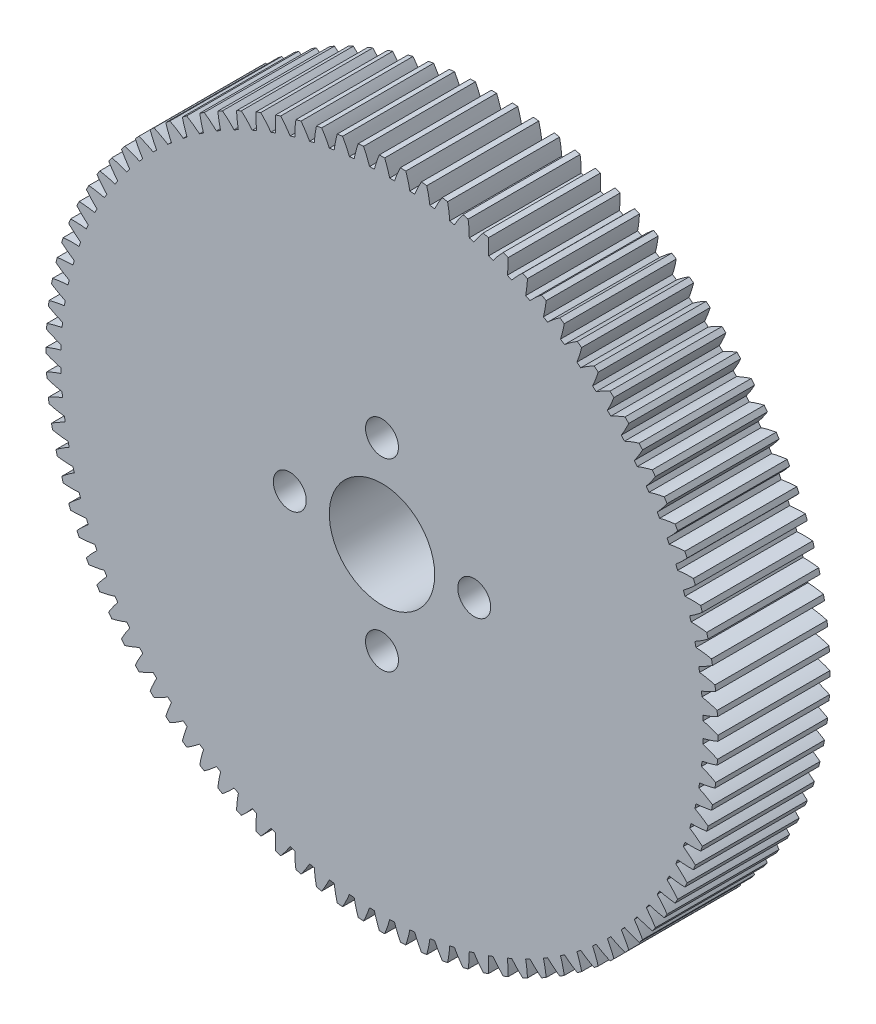
SolidWorks part; units mm, degrees
material "ABS"
ref_plane "Front Plane" through (0, 0, 0) normal (0, 0, 1) x (1, 0, 0)
ref_plane "Top Plane" through (0, 0, 0) normal (0, 1, 0) x (1, 0, 0)
ref_plane "Right Plane" through (0, 0, 0) normal (1, 0, 0) x (0, 0, -1)
ref_plane "Plane1" through (0, 0, 4) normal (0, 0, 1) x (1, 0, 0)
sketch "Sketch1" plane through (0, 0, 4) normal (0, 0, 1) x (1, 0, 0)
  line L0 (25.4992, -0.2018) -> (25.4992, 0.2018)
  line L1 (25.4616, 1.3997) -> (25.4362, 1.8025)
  line L2 (25.3234, 2.9957) -> (25.2728, 3.3961)
  line L3 (25.0854, 4.5799) -> (25.0097, 4.9763)
  line L4 (24.7483, 6.1459) -> (24.6479, 6.5369)
  line L5 (24.3135, 7.6878) -> (24.1888, 8.0716)
  line L6 (23.7828, 9.1993) -> (23.6343, 9.5745)
  line L7 (23.1583, 10.6744) -> (22.9864, 11.0396)
  line L8 (22.4423, 12.1075) -> (22.2479, 12.4612)
  line L9 (21.6378, 13.4928) -> (21.4216, 13.8335)
  line L10 (20.7479, 14.8248) -> (20.5107, 15.1513)
  line L11 (19.7761, 16.0983) -> (19.5188, 16.4093)
  line L12 (18.7263, 17.3083) -> (18.45, 17.6025)
  line L13 (17.6025, 18.45) -> (17.3083, 18.7263)
  line L14 (16.4093, 19.5188) -> (16.0983, 19.7761)
  line L15 (15.1513, 20.5107) -> (14.8248, 20.7479)
  line L16 (13.8335, 21.4216) -> (13.4928, 21.6378)
  line L17 (12.4612, 22.2479) -> (12.1075, 22.4423)
  line L18 (11.0396, 22.9864) -> (10.6744, 23.1583)
  line L19 (9.5745, 23.6343) -> (9.1993, 23.7828)
  line L20 (8.0716, 24.1888) -> (7.6878, 24.3135)
  line L21 (6.5369, 24.6479) -> (6.1459, 24.7483)
  line L22 (4.9763, 25.0097) -> (4.5799, 25.0854)
  line L23 (3.3961, 25.2728) -> (2.9957, 25.3234)
  line L24 (1.8025, 25.4362) -> (1.3997, 25.4616)
  line L25 (0.2018, 25.4992) -> (-0.2018, 25.4992)
  line L26 (-1.3997, 25.4616) -> (-1.8025, 25.4362)
  line L27 (-2.9957, 25.3234) -> (-3.3961, 25.2728)
  line L28 (-4.5799, 25.0854) -> (-4.9763, 25.0097)
  line L29 (-6.1459, 24.7483) -> (-6.5369, 24.6479)
  line L30 (-7.6878, 24.3135) -> (-8.0716, 24.1888)
  line L31 (-9.1993, 23.7828) -> (-9.5745, 23.6343)
  line L32 (-10.6744, 23.1583) -> (-11.0396, 22.9864)
  line L33 (-12.1075, 22.4423) -> (-12.4612, 22.2479)
  line L34 (-13.4928, 21.6378) -> (-13.8335, 21.4216)
  line L35 (-14.8248, 20.7479) -> (-15.1513, 20.5107)
  line L36 (-16.0983, 19.7761) -> (-16.4093, 19.5188)
  line L37 (-17.3083, 18.7263) -> (-17.6025, 18.45)
  line L38 (-18.45, 17.6025) -> (-18.7263, 17.3083)
  line L39 (-19.5188, 16.4093) -> (-19.7761, 16.0983)
  line L40 (-20.5107, 15.1513) -> (-20.7479, 14.8248)
  line L41 (-21.4216, 13.8335) -> (-21.6378, 13.4928)
  line L42 (-22.2479, 12.4612) -> (-22.4423, 12.1075)
  line L43 (-22.9864, 11.0396) -> (-23.1583, 10.6744)
  line L44 (-23.6343, 9.5745) -> (-23.7828, 9.1993)
  line L45 (-24.1888, 8.0716) -> (-24.3135, 7.6878)
  line L46 (-24.6479, 6.5369) -> (-24.7483, 6.1459)
  line L47 (-25.0097, 4.9763) -> (-25.0854, 4.5799)
  line L48 (-25.2728, 3.3961) -> (-25.3234, 2.9957)
  line L49 (-25.4362, 1.8025) -> (-25.4616, 1.3997)
  line L50 (-25.4992, 0.2018) -> (-25.4992, -0.2018)
  line L51 (-25.4616, -1.3997) -> (-25.4362, -1.8025)
  line L52 (-25.3234, -2.9957) -> (-25.2728, -3.3961)
  line L53 (-25.0854, -4.5799) -> (-25.0097, -4.9763)
  line L54 (-24.7483, -6.1459) -> (-24.6479, -6.5369)
  line L55 (-24.3135, -7.6878) -> (-24.1888, -8.0716)
  line L56 (-23.7828, -9.1993) -> (-23.6343, -9.5745)
  line L57 (-23.1583, -10.6744) -> (-22.9864, -11.0396)
  line L58 (-22.4423, -12.1075) -> (-22.2479, -12.4612)
  line L59 (-21.6378, -13.4928) -> (-21.4216, -13.8335)
  line L60 (-20.7479, -14.8248) -> (-20.5107, -15.1513)
  line L61 (-19.7761, -16.0983) -> (-19.5188, -16.4093)
  line L62 (-18.7263, -17.3083) -> (-18.45, -17.6025)
  line L63 (-17.6025, -18.45) -> (-17.3083, -18.7263)
  line L64 (-16.4093, -19.5188) -> (-16.0983, -19.7761)
  line L65 (-15.1513, -20.5107) -> (-14.8248, -20.7479)
  line L66 (-13.8335, -21.4216) -> (-13.4928, -21.6378)
  line L67 (-12.4612, -22.2479) -> (-12.1075, -22.4423)
  line L68 (-11.0396, -22.9864) -> (-10.6744, -23.1583)
  line L69 (-9.5745, -23.6343) -> (-9.1993, -23.7828)
  line L70 (-8.0716, -24.1888) -> (-7.6878, -24.3135)
  line L71 (-6.5369, -24.6479) -> (-6.1459, -24.7483)
  line L72 (-4.9763, -25.0097) -> (-4.5799, -25.0854)
  line L73 (-3.3961, -25.2728) -> (-2.9957, -25.3234)
  line L74 (-1.8025, -25.4362) -> (-1.3997, -25.4616)
  line L75 (-0.2018, -25.4992) -> (0.2018, -25.4992)
  line L76 (1.3997, -25.4616) -> (1.8025, -25.4362)
  line L77 (2.9957, -25.3234) -> (3.3961, -25.2728)
  line L78 (4.5799, -25.0854) -> (4.9763, -25.0097)
  line L79 (6.1459, -24.7483) -> (6.5369, -24.6479)
  line L80 (7.6878, -24.3135) -> (8.0716, -24.1888)
  line L81 (9.1993, -23.7828) -> (9.5745, -23.6343)
  line L82 (10.6744, -23.1583) -> (11.0396, -22.9864)
  line L83 (12.1075, -22.4423) -> (12.4612, -22.2479)
  line L84 (13.4928, -21.6378) -> (13.8335, -21.4216)
  line L85 (14.8248, -20.7479) -> (15.1513, -20.5107)
  line L86 (16.0983, -19.7761) -> (16.4093, -19.5188)
  line L87 (17.3083, -18.7263) -> (17.6025, -18.45)
  line L88 (18.45, -17.6025) -> (18.7263, -17.3083)
  line L89 (19.5188, -16.4093) -> (19.7761, -16.0983)
  line L90 (20.5107, -15.1513) -> (20.7479, -14.8248)
  line L91 (21.4216, -13.8335) -> (21.6378, -13.4928)
  line L92 (22.2479, -12.4612) -> (22.4423, -12.1075)
  line L93 (22.9864, -11.0396) -> (23.1583, -10.6744)
  line L94 (23.6343, -9.5745) -> (23.7828, -9.1993)
  line L95 (24.1888, -8.0716) -> (24.3135, -7.6878)
  line L96 (24.6479, -6.5369) -> (24.7483, -6.1459)
  line L97 (25.0097, -4.9763) -> (25.0854, -4.5799)
  line L98 (25.2728, -3.3961) -> (25.3234, -2.9957)
  line L99 (25.4362, -1.8025) -> (25.4616, -1.3997)
  arc A0 (24.3565, -0.9497) -> (24.3681, -0.5815) centre (0, 0) ccw
  arc A1 (24.3681, -0.5815) -> (25.4992, -0.2018) centre (22.3084, 7.4288) ccw
  arc A2 (25.4992, 0.2018) -> (24.3681, 0.5815) centre (22.3272, -7.3729) ccw
  arc A3 (24.3681, 0.5815) -> (24.3565, 0.9497) centre (0, 0) ccw
  arc A4 (24.3565, 0.9497) -> (25.4616, 1.3997) centre (21.7979, 8.8149) ccw
  arc A5 (25.4362, 1.8025) -> (24.2835, 2.1104) centre (22.7461, -5.9564) ccw
  arc A6 (24.2835, 2.1104) -> (24.2488, 2.4772) centre (0, 0) ccw
  arc A7 (24.2488, 2.4772) -> (25.3234, 2.9957) centre (21.2014, 10.1662) ccw
  arc A8 (25.2728, 3.3961) -> (24.103, 3.631) centre (23.0752, -4.5164) ccw
  arc A9 (24.103, 3.631) -> (24.0454, 3.9949) centre (0, 0) ccw
  arc A10 (24.0454, 3.9949) -> (25.0854, 4.5799) centre (20.5213, 11.4774) ccw
  arc A11 (25.0097, 4.9763) -> (23.8275, 5.1373) centre (23.3132, -3.0586) ccw
  arc A12 (23.8275, 5.1373) -> (23.7471, 5.4969) centre (0, 0) ccw
  arc A13 (23.7471, 5.4969) -> (24.7483, 6.1459) centre (19.7601, 12.7433) ccw
  arc A14 (24.6479, 6.5369) -> (23.4579, 6.6233) centre (23.4593, -1.5887) ccw
  arc A15 (23.4579, 6.6233) -> (23.3551, 6.9771) centre (0, 0) ccw
  arc A16 (23.3551, 6.9771) -> (24.3135, 7.6878) centre (18.921, 13.9589) ccw
  arc A17 (24.1888, 8.0716) -> (22.9957, 8.0832) centre (23.5128, -0.1125) ccw
  arc A18 (22.9957, 8.0832) -> (22.8709, 8.4298) centre (0, 0) ccw
  arc A19 (22.8709, 8.4298) -> (23.7828, 9.1993) centre (18.0071, 15.1194) ccw
  arc A20 (23.6343, 9.5745) -> (22.4428, 9.5112) centre (23.4734, 1.3641) ccw
  arc A21 (22.4428, 9.5112) -> (22.2965, 9.8493) centre (0, 0) ccw
  arc A22 (22.2965, 9.8493) -> (23.1583, 10.6744) centre (17.0222, 16.2202) ccw
  arc A23 (22.9864, 11.0396) -> (21.8013, 10.9016) centre (23.3415, 2.8353) ccw
  arc A24 (21.8013, 10.9016) -> (21.634, 11.2298) centre (0, 0) ccw
  arc A25 (21.634, 11.2298) -> (22.4423, 12.1075) centre (15.9702, 17.257) ccw
  arc A26 (22.2479, 12.4612) -> (21.0738, 12.249) centre (23.1174, 4.2953) ccw
  arc A27 (21.0738, 12.249) -> (20.8862, 12.5661) centre (0, 0) ccw
  arc A28 (20.8862, 12.5661) -> (21.6378, 13.4928) centre (14.8551, 18.2258) ccw
  arc A29 (21.4216, 13.8335) -> (20.263, 13.548) centre (22.8021, 5.7384) ccw
  arc A30 (20.263, 13.548) -> (20.056, 13.8527) centre (0, 0) ccw
  arc A31 (20.056, 13.8527) -> (20.7479, 14.8248) centre (13.6814, 19.1226) ccw
  arc A32 (20.5107, 15.1513) -> (19.3724, 14.7936) centre (22.3967, 7.1588) ccw
  arc A33 (19.3724, 14.7936) -> (19.1466, 15.0847) centre (0, 0) ccw
  arc A34 (19.1466, 15.0847) -> (19.7761, 16.0983) centre (12.4537, 19.9439) ccw
  arc A35 (19.5188, 16.4093) -> (18.4052, 15.9808) centre (21.903, 8.551) ccw
  arc A36 (18.4052, 15.9808) -> (18.1616, 16.2572) centre (0, 0) ccw
  arc A37 (18.1616, 16.2572) -> (18.7263, 17.3083) centre (11.1768, 20.6865) ccw
  arc A38 (18.45, 17.6025) -> (17.3655, 17.105) centre (21.3229, 9.9094) ccw
  arc A39 (17.3655, 17.105) -> (17.105, 17.3655) centre (0, 0) ccw
  arc A40 (17.105, 17.3655) -> (17.6025, 18.45) centre (9.8558, 21.3475) ccw
  arc A41 (17.3083, 18.7263) -> (16.2572, 18.1616) centre (20.6586, 11.2287) ccw
  arc A42 (16.2572, 18.1616) -> (15.9808, 18.4052) centre (0, 0) ccw
  arc A43 (15.9808, 18.4052) -> (16.4093, 19.5188) centre (8.496, 21.9242) ccw
  arc A44 (16.0983, 19.7761) -> (15.0847, 19.1466) centre (19.9128, 12.5037) ccw
  arc A45 (15.0847, 19.1466) -> (14.7936, 19.3724) centre (0, 0) ccw
  arc A46 (14.7936, 19.3724) -> (15.1513, 20.5107) centre (7.1026, 22.4144) ccw
  arc A47 (14.8248, 20.7479) -> (13.8527, 20.056) centre (19.0884, 13.7294) ccw
  arc A48 (13.8527, 20.056) -> (13.548, 20.263) centre (0, 0) ccw
  arc A49 (13.548, 20.263) -> (13.8335, 21.4216) centre (5.6811, 22.8162) ccw
  arc A50 (13.4928, 21.6378) -> (12.5661, 20.8862) centre (18.1886, 14.9009) ccw
  arc A51 (12.5661, 20.8862) -> (12.249, 21.0738) centre (0, 0) ccw
  arc A52 (12.249, 21.0738) -> (12.4612, 22.2479) centre (4.2373, 23.1279) ccw
  arc A53 (12.1075, 22.4423) -> (11.2298, 21.634) centre (17.2171, 16.0136) ccw
  arc A54 (11.2298, 21.634) -> (10.9016, 21.8013) centre (0, 0) ccw
  arc A55 (10.9016, 21.8013) -> (11.0396, 22.9864) centre (2.7767, 23.3483) ccw
  arc A56 (10.6744, 23.1583) -> (9.8493, 22.2965) centre (16.1776, 17.063) ccw
  arc A57 (9.8493, 22.2965) -> (9.5112, 22.4428) centre (0, 0) ccw
  arc A58 (9.5112, 22.4428) -> (9.5745, 23.6343) centre (1.3052, 23.4766) ccw
  arc A59 (9.1993, 23.7828) -> (8.4298, 22.8709) centre (15.0743, 18.0452) ccw
  arc A60 (8.4298, 22.8709) -> (8.0832, 22.9957) centre (0, 0) ccw
  arc A61 (8.0832, 22.9957) -> (8.0716, 24.1888) centre (-0.1715, 23.5122) ccw
  arc A62 (7.6878, 24.3135) -> (6.9771, 23.3551) centre (13.9115, 18.9561) ccw
  arc A63 (6.9771, 23.3551) -> (6.6233, 23.4579) centre (0, 0) ccw
  arc A64 (6.6233, 23.4579) -> (6.5369, 24.6479) centre (-1.6475, 23.455) ccw
  arc A65 (6.1459, 24.7483) -> (5.4969, 23.7471) centre (12.6938, 19.7922) ccw
  arc A66 (5.4969, 23.7471) -> (5.1373, 23.8275) centre (0, 0) ccw
  arc A67 (5.1373, 23.8275) -> (4.9763, 25.0097) centre (-3.117, 23.3053) ccw
  arc A68 (4.5799, 25.0854) -> (3.9949, 24.0454) centre (11.426, 20.5502) ccw
  arc A69 (3.9949, 24.0454) -> (3.631, 24.103) centre (0, 0) ccw
  arc A70 (3.631, 24.103) -> (3.3961, 25.2728) centre (-4.5742, 23.0636) ccw
  arc A71 (2.9957, 25.3234) -> (2.4772, 24.2488) centre (10.1131, 21.2271) ccw
  arc A72 (2.4772, 24.2488) -> (2.1104, 24.2835) centre (0, 0) ccw
  arc A73 (2.1104, 24.2835) -> (1.8025, 25.4362) centre (-6.0134, 22.7309) ccw
  arc A74 (1.3997, 25.4616) -> (0.9497, 24.3565) centre (8.7603, 21.8202) ccw
  arc A75 (0.9497, 24.3565) -> (0.5815, 24.3681) centre (0, 0) ccw
  arc A76 (0.5815, 24.3681) -> (0.2018, 25.4992) centre (-7.4288, 22.3084) ccw
  arc A77 (-0.2018, 25.4992) -> (-0.5815, 24.3681) centre (7.3729, 22.3272) ccw
  arc A78 (-0.5815, 24.3681) -> (-0.9497, 24.3565) centre (0, 0) ccw
  arc A79 (-0.9497, 24.3565) -> (-1.3997, 25.4616) centre (-8.8149, 21.7979) ccw
  arc A80 (-1.8025, 25.4362) -> (-2.1104, 24.2835) centre (5.9564, 22.7461) ccw
  arc A81 (-2.1104, 24.2835) -> (-2.4772, 24.2488) centre (0, 0) ccw
  arc A82 (-2.4772, 24.2488) -> (-2.9957, 25.3234) centre (-10.1662, 21.2014) ccw
  arc A83 (-3.3961, 25.2728) -> (-3.631, 24.103) centre (4.5164, 23.0752) ccw
  arc A84 (-3.631, 24.103) -> (-3.9949, 24.0454) centre (0, 0) ccw
  arc A85 (-3.9949, 24.0454) -> (-4.5799, 25.0854) centre (-11.4774, 20.5213) ccw
  arc A86 (-4.9763, 25.0097) -> (-5.1373, 23.8275) centre (3.0586, 23.3132) ccw
  arc A87 (-5.1373, 23.8275) -> (-5.4969, 23.7471) centre (0, 0) ccw
  arc A88 (-5.4969, 23.7471) -> (-6.1459, 24.7483) centre (-12.7433, 19.7601) ccw
  arc A89 (-6.5369, 24.6479) -> (-6.6233, 23.4579) centre (1.5887, 23.4593) ccw
  arc A90 (-6.6233, 23.4579) -> (-6.9771, 23.3551) centre (0, 0) ccw
  arc A91 (-6.9771, 23.3551) -> (-7.6878, 24.3135) centre (-13.9589, 18.921) ccw
  arc A92 (-8.0716, 24.1888) -> (-8.0832, 22.9957) centre (0.1125, 23.5128) ccw
  arc A93 (-8.0832, 22.9957) -> (-8.4298, 22.8709) centre (0, 0) ccw
  arc A94 (-8.4298, 22.8709) -> (-9.1993, 23.7828) centre (-15.1194, 18.0071) ccw
  arc A95 (-9.5745, 23.6343) -> (-9.5112, 22.4428) centre (-1.3641, 23.4734) ccw
  arc A96 (-9.5112, 22.4428) -> (-9.8493, 22.2965) centre (0, 0) ccw
  arc A97 (-9.8493, 22.2965) -> (-10.6744, 23.1583) centre (-16.2202, 17.0222) ccw
  arc A98 (-11.0396, 22.9864) -> (-10.9016, 21.8013) centre (-2.8353, 23.3415) ccw
  arc A99 (-10.9016, 21.8013) -> (-11.2298, 21.634) centre (0, 0) ccw
  arc A100 (-11.2298, 21.634) -> (-12.1075, 22.4423) centre (-17.257, 15.9702) ccw
  arc A101 (-12.4612, 22.2479) -> (-12.249, 21.0738) centre (-4.2953, 23.1174) ccw
  arc A102 (-12.249, 21.0738) -> (-12.5661, 20.8862) centre (0, 0) ccw
  arc A103 (-12.5661, 20.8862) -> (-13.4928, 21.6378) centre (-18.2258, 14.8551) ccw
  arc A104 (-13.8335, 21.4216) -> (-13.548, 20.263) centre (-5.7384, 22.8021) ccw
  arc A105 (-13.548, 20.263) -> (-13.8527, 20.056) centre (0, 0) ccw
  arc A106 (-13.8527, 20.056) -> (-14.8248, 20.7479) centre (-19.1226, 13.6814) ccw
  arc A107 (-15.1513, 20.5107) -> (-14.7936, 19.3724) centre (-7.1588, 22.3967) ccw
  arc A108 (-14.7936, 19.3724) -> (-15.0847, 19.1466) centre (0, 0) ccw
  arc A109 (-15.0847, 19.1466) -> (-16.0983, 19.7761) centre (-19.9439, 12.4537) ccw
  arc A110 (-16.4093, 19.5188) -> (-15.9808, 18.4052) centre (-8.551, 21.903) ccw
  arc A111 (-15.9808, 18.4052) -> (-16.2572, 18.1616) centre (0, 0) ccw
  arc A112 (-16.2572, 18.1616) -> (-17.3083, 18.7263) centre (-20.6865, 11.1768) ccw
  arc A113 (-17.6025, 18.45) -> (-17.105, 17.3655) centre (-9.9094, 21.3229) ccw
  arc A114 (-17.105, 17.3655) -> (-17.3655, 17.105) centre (0, 0) ccw
  arc A115 (-17.3655, 17.105) -> (-18.45, 17.6025) centre (-21.3475, 9.8558) ccw
  arc A116 (-18.7263, 17.3083) -> (-18.1616, 16.2572) centre (-11.2287, 20.6586) ccw
  arc A117 (-18.1616, 16.2572) -> (-18.4052, 15.9808) centre (0, 0) ccw
  arc A118 (-18.4052, 15.9808) -> (-19.5188, 16.4093) centre (-21.9242, 8.496) ccw
  arc A119 (-19.7761, 16.0983) -> (-19.1466, 15.0847) centre (-12.5037, 19.9128) ccw
  arc A120 (-19.1466, 15.0847) -> (-19.3724, 14.7936) centre (0, 0) ccw
  arc A121 (-19.3724, 14.7936) -> (-20.5107, 15.1513) centre (-22.4144, 7.1026) ccw
  arc A122 (-20.7479, 14.8248) -> (-20.056, 13.8527) centre (-13.7294, 19.0884) ccw
  arc A123 (-20.056, 13.8527) -> (-20.263, 13.548) centre (0, 0) ccw
  arc A124 (-20.263, 13.548) -> (-21.4216, 13.8335) centre (-22.8162, 5.6811) ccw
  arc A125 (-21.6378, 13.4928) -> (-20.8862, 12.5661) centre (-14.9009, 18.1886) ccw
  arc A126 (-20.8862, 12.5661) -> (-21.0738, 12.249) centre (0, 0) ccw
  arc A127 (-21.0738, 12.249) -> (-22.2479, 12.4612) centre (-23.1279, 4.2373) ccw
  arc A128 (-22.4423, 12.1075) -> (-21.634, 11.2298) centre (-16.0136, 17.2171) ccw
  arc A129 (-21.634, 11.2298) -> (-21.8013, 10.9016) centre (0, 0) ccw
  arc A130 (-21.8013, 10.9016) -> (-22.9864, 11.0396) centre (-23.3483, 2.7767) ccw
  arc A131 (-23.1583, 10.6744) -> (-22.2965, 9.8493) centre (-17.063, 16.1776) ccw
  arc A132 (-22.2965, 9.8493) -> (-22.4428, 9.5112) centre (0, 0) ccw
  arc A133 (-22.4428, 9.5112) -> (-23.6343, 9.5745) centre (-23.4766, 1.3052) ccw
  arc A134 (-23.7828, 9.1993) -> (-22.8709, 8.4298) centre (-18.0452, 15.0743) ccw
  arc A135 (-22.8709, 8.4298) -> (-22.9957, 8.0832) centre (0, 0) ccw
  arc A136 (-22.9957, 8.0832) -> (-24.1888, 8.0716) centre (-23.5122, -0.1715) ccw
  arc A137 (-24.3135, 7.6878) -> (-23.3551, 6.9771) centre (-18.9561, 13.9115) ccw
  arc A138 (-23.3551, 6.9771) -> (-23.4579, 6.6233) centre (0, 0) ccw
  arc A139 (-23.4579, 6.6233) -> (-24.6479, 6.5369) centre (-23.455, -1.6475) ccw
  arc A140 (-24.7483, 6.1459) -> (-23.7471, 5.4969) centre (-19.7922, 12.6938) ccw
  arc A141 (-23.7471, 5.4969) -> (-23.8275, 5.1373) centre (0, 0) ccw
  arc A142 (-23.8275, 5.1373) -> (-25.0097, 4.9763) centre (-23.3053, -3.117) ccw
  arc A143 (-25.0854, 4.5799) -> (-24.0454, 3.9949) centre (-20.5502, 11.426) ccw
  arc A144 (-24.0454, 3.9949) -> (-24.103, 3.631) centre (0, 0) ccw
  arc A145 (-24.103, 3.631) -> (-25.2728, 3.3961) centre (-23.0636, -4.5742) ccw
  arc A146 (-25.3234, 2.9957) -> (-24.2488, 2.4772) centre (-21.2271, 10.1131) ccw
  arc A147 (-24.2488, 2.4772) -> (-24.2835, 2.1104) centre (0, 0) ccw
  arc A148 (-24.2835, 2.1104) -> (-25.4362, 1.8025) centre (-22.7309, -6.0134) ccw
  arc A149 (-25.4616, 1.3997) -> (-24.3565, 0.9497) centre (-21.8202, 8.7603) ccw
  arc A150 (-24.3565, 0.9497) -> (-24.3681, 0.5815) centre (0, 0) ccw
  arc A151 (-24.3681, 0.5815) -> (-25.4992, 0.2018) centre (-22.3084, -7.4288) ccw
  arc A152 (-25.4992, -0.2018) -> (-24.3681, -0.5815) centre (-22.3272, 7.3729) ccw
  arc A153 (-24.3681, -0.5815) -> (-24.3565, -0.9497) centre (0, 0) ccw
  arc A154 (-24.3565, -0.9497) -> (-25.4616, -1.3997) centre (-21.7979, -8.8149) ccw
  arc A155 (-25.4362, -1.8025) -> (-24.2835, -2.1104) centre (-22.7461, 5.9564) ccw
  arc A156 (-24.2835, -2.1104) -> (-24.2488, -2.4772) centre (0, 0) ccw
  arc A157 (-24.2488, -2.4772) -> (-25.3234, -2.9957) centre (-21.2014, -10.1662) ccw
  arc A158 (-25.2728, -3.3961) -> (-24.103, -3.631) centre (-23.0752, 4.5164) ccw
  arc A159 (-24.103, -3.631) -> (-24.0454, -3.9949) centre (0, 0) ccw
  arc A160 (-24.0454, -3.9949) -> (-25.0854, -4.5799) centre (-20.5213, -11.4774) ccw
  arc A161 (-25.0097, -4.9763) -> (-23.8275, -5.1373) centre (-23.3132, 3.0586) ccw
  arc A162 (-23.8275, -5.1373) -> (-23.7471, -5.4969) centre (0, 0) ccw
  arc A163 (-23.7471, -5.4969) -> (-24.7483, -6.1459) centre (-19.7601, -12.7433) ccw
  arc A164 (-24.6479, -6.5369) -> (-23.4579, -6.6233) centre (-23.4593, 1.5887) ccw
  arc A165 (-23.4579, -6.6233) -> (-23.3551, -6.9771) centre (0, 0) ccw
  arc A166 (-23.3551, -6.9771) -> (-24.3135, -7.6878) centre (-18.921, -13.9589) ccw
  arc A167 (-24.1888, -8.0716) -> (-22.9957, -8.0832) centre (-23.5128, 0.1125) ccw
  arc A168 (-22.9957, -8.0832) -> (-22.8709, -8.4298) centre (0, 0) ccw
  arc A169 (-22.8709, -8.4298) -> (-23.7828, -9.1993) centre (-18.0071, -15.1194) ccw
  arc A170 (-23.6343, -9.5745) -> (-22.4428, -9.5112) centre (-23.4734, -1.3641) ccw
  arc A171 (-22.4428, -9.5112) -> (-22.2965, -9.8493) centre (0, 0) ccw
  arc A172 (-22.2965, -9.8493) -> (-23.1583, -10.6744) centre (-17.0222, -16.2202) ccw
  arc A173 (-22.9864, -11.0396) -> (-21.8013, -10.9016) centre (-23.3415, -2.8353) ccw
  arc A174 (-21.8013, -10.9016) -> (-21.634, -11.2298) centre (0, 0) ccw
  arc A175 (-21.634, -11.2298) -> (-22.4423, -12.1075) centre (-15.9702, -17.257) ccw
  arc A176 (-22.2479, -12.4612) -> (-21.0738, -12.249) centre (-23.1174, -4.2953) ccw
  arc A177 (-21.0738, -12.249) -> (-20.8862, -12.5661) centre (0, 0) ccw
  arc A178 (-20.8862, -12.5661) -> (-21.6378, -13.4928) centre (-14.8551, -18.2258) ccw
  arc A179 (-21.4216, -13.8335) -> (-20.263, -13.548) centre (-22.8021, -5.7384) ccw
  arc A180 (-20.263, -13.548) -> (-20.056, -13.8527) centre (0, 0) ccw
  arc A181 (-20.056, -13.8527) -> (-20.7479, -14.8248) centre (-13.6814, -19.1226) ccw
  arc A182 (-20.5107, -15.1513) -> (-19.3724, -14.7936) centre (-22.3967, -7.1588) ccw
  arc A183 (-19.3724, -14.7936) -> (-19.1466, -15.0847) centre (0, 0) ccw
  arc A184 (-19.1466, -15.0847) -> (-19.7761, -16.0983) centre (-12.4537, -19.9439) ccw
  arc A185 (-19.5188, -16.4093) -> (-18.4052, -15.9808) centre (-21.903, -8.551) ccw
  arc A186 (-18.4052, -15.9808) -> (-18.1616, -16.2572) centre (0, 0) ccw
  arc A187 (-18.1616, -16.2572) -> (-18.7263, -17.3083) centre (-11.1768, -20.6865) ccw
  arc A188 (-18.45, -17.6025) -> (-17.3655, -17.105) centre (-21.3229, -9.9094) ccw
  arc A189 (-17.3655, -17.105) -> (-17.105, -17.3655) centre (0, 0) ccw
  arc A190 (-17.105, -17.3655) -> (-17.6025, -18.45) centre (-9.8558, -21.3475) ccw
  arc A191 (-17.3083, -18.7263) -> (-16.2572, -18.1616) centre (-20.6586, -11.2287) ccw
  arc A192 (-16.2572, -18.1616) -> (-15.9808, -18.4052) centre (0, 0) ccw
  arc A193 (-15.9808, -18.4052) -> (-16.4093, -19.5188) centre (-8.496, -21.9242) ccw
  arc A194 (-16.0983, -19.7761) -> (-15.0847, -19.1466) centre (-19.9128, -12.5037) ccw
  arc A195 (-15.0847, -19.1466) -> (-14.7936, -19.3724) centre (0, 0) ccw
  arc A196 (-14.7936, -19.3724) -> (-15.1513, -20.5107) centre (-7.1026, -22.4144) ccw
  arc A197 (-14.8248, -20.7479) -> (-13.8527, -20.056) centre (-19.0884, -13.7294) ccw
  arc A198 (-13.8527, -20.056) -> (-13.548, -20.263) centre (0, 0) ccw
  arc A199 (-13.548, -20.263) -> (-13.8335, -21.4216) centre (-5.6811, -22.8162) ccw
  arc A200 (-13.4928, -21.6378) -> (-12.5661, -20.8862) centre (-18.1886, -14.9009) ccw
  arc A201 (-12.5661, -20.8862) -> (-12.249, -21.0738) centre (0, 0) ccw
  arc A202 (-12.249, -21.0738) -> (-12.4612, -22.2479) centre (-4.2373, -23.1279) ccw
  arc A203 (-12.1075, -22.4423) -> (-11.2298, -21.634) centre (-17.2171, -16.0136) ccw
  arc A204 (-11.2298, -21.634) -> (-10.9016, -21.8013) centre (0, 0) ccw
  arc A205 (-10.9016, -21.8013) -> (-11.0396, -22.9864) centre (-2.7767, -23.3483) ccw
  arc A206 (-10.6744, -23.1583) -> (-9.8493, -22.2965) centre (-16.1776, -17.063) ccw
  arc A207 (-9.8493, -22.2965) -> (-9.5112, -22.4428) centre (0, 0) ccw
  arc A208 (-9.5112, -22.4428) -> (-9.5745, -23.6343) centre (-1.3052, -23.4766) ccw
  arc A209 (-9.1993, -23.7828) -> (-8.4298, -22.8709) centre (-15.0743, -18.0452) ccw
  arc A210 (-8.4298, -22.8709) -> (-8.0832, -22.9957) centre (0, 0) ccw
  arc A211 (-8.0832, -22.9957) -> (-8.0716, -24.1888) centre (0.1715, -23.5122) ccw
  arc A212 (-7.6878, -24.3135) -> (-6.9771, -23.3551) centre (-13.9115, -18.9561) ccw
  arc A213 (-6.9771, -23.3551) -> (-6.6233, -23.4579) centre (0, 0) ccw
  arc A214 (-6.6233, -23.4579) -> (-6.5369, -24.6479) centre (1.6475, -23.455) ccw
  arc A215 (-6.1459, -24.7483) -> (-5.4969, -23.7471) centre (-12.6938, -19.7922) ccw
  arc A216 (-5.4969, -23.7471) -> (-5.1373, -23.8275) centre (0, 0) ccw
  arc A217 (-5.1373, -23.8275) -> (-4.9763, -25.0097) centre (3.117, -23.3053) ccw
  arc A218 (-4.5799, -25.0854) -> (-3.9949, -24.0454) centre (-11.426, -20.5502) ccw
  arc A219 (-3.9949, -24.0454) -> (-3.631, -24.103) centre (0, 0) ccw
  arc A220 (-3.631, -24.103) -> (-3.3961, -25.2728) centre (4.5742, -23.0636) ccw
  arc A221 (-2.9957, -25.3234) -> (-2.4772, -24.2488) centre (-10.1131, -21.2271) ccw
  arc A222 (-2.4772, -24.2488) -> (-2.1104, -24.2835) centre (0, 0) ccw
  arc A223 (-2.1104, -24.2835) -> (-1.8025, -25.4362) centre (6.0134, -22.7309) ccw
  arc A224 (-1.3997, -25.4616) -> (-0.9497, -24.3565) centre (-8.7603, -21.8202) ccw
  arc A225 (-0.9497, -24.3565) -> (-0.5815, -24.3681) centre (0, 0) ccw
  arc A226 (-0.5815, -24.3681) -> (-0.2018, -25.4992) centre (7.4288, -22.3084) ccw
  arc A227 (0.2018, -25.4992) -> (0.5815, -24.3681) centre (-7.3729, -22.3272) ccw
  arc A228 (0.5815, -24.3681) -> (0.9497, -24.3565) centre (0, 0) ccw
  arc A229 (0.9497, -24.3565) -> (1.3997, -25.4616) centre (8.8149, -21.7979) ccw
  arc A230 (1.8025, -25.4362) -> (2.1104, -24.2835) centre (-5.9564, -22.7461) ccw
  arc A231 (2.1104, -24.2835) -> (2.4772, -24.2488) centre (0, 0) ccw
  arc A232 (2.4772, -24.2488) -> (2.9957, -25.3234) centre (10.1662, -21.2014) ccw
  arc A233 (3.3961, -25.2728) -> (3.631, -24.103) centre (-4.5164, -23.0752) ccw
  arc A234 (3.631, -24.103) -> (3.9949, -24.0454) centre (0, 0) ccw
  arc A235 (3.9949, -24.0454) -> (4.5799, -25.0854) centre (11.4774, -20.5213) ccw
  arc A236 (4.9763, -25.0097) -> (5.1373, -23.8275) centre (-3.0586, -23.3132) ccw
  arc A237 (5.1373, -23.8275) -> (5.4969, -23.7471) centre (0, 0) ccw
  arc A238 (5.4969, -23.7471) -> (6.1459, -24.7483) centre (12.7433, -19.7601) ccw
  arc A239 (6.5369, -24.6479) -> (6.6233, -23.4579) centre (-1.5887, -23.4593) ccw
  arc A240 (6.6233, -23.4579) -> (6.9771, -23.3551) centre (0, 0) ccw
  arc A241 (6.9771, -23.3551) -> (7.6878, -24.3135) centre (13.9589, -18.921) ccw
  arc A242 (8.0716, -24.1888) -> (8.0832, -22.9957) centre (-0.1125, -23.5128) ccw
  arc A243 (8.0832, -22.9957) -> (8.4298, -22.8709) centre (0, 0) ccw
  arc A244 (8.4298, -22.8709) -> (9.1993, -23.7828) centre (15.1194, -18.0071) ccw
  arc A245 (9.5745, -23.6343) -> (9.5112, -22.4428) centre (1.3641, -23.4734) ccw
  arc A246 (9.5112, -22.4428) -> (9.8493, -22.2965) centre (0, 0) ccw
  arc A247 (9.8493, -22.2965) -> (10.6744, -23.1583) centre (16.2202, -17.0222) ccw
  arc A248 (11.0396, -22.9864) -> (10.9016, -21.8013) centre (2.8353, -23.3415) ccw
  arc A249 (10.9016, -21.8013) -> (11.2298, -21.634) centre (0, 0) ccw
  arc A250 (11.2298, -21.634) -> (12.1075, -22.4423) centre (17.257, -15.9702) ccw
  arc A251 (12.4612, -22.2479) -> (12.249, -21.0738) centre (4.2953, -23.1174) ccw
  arc A252 (12.249, -21.0738) -> (12.5661, -20.8862) centre (0, 0) ccw
  arc A253 (12.5661, -20.8862) -> (13.4928, -21.6378) centre (18.2258, -14.8551) ccw
  arc A254 (13.8335, -21.4216) -> (13.548, -20.263) centre (5.7384, -22.8021) ccw
  arc A255 (13.548, -20.263) -> (13.8527, -20.056) centre (0, 0) ccw
  arc A256 (13.8527, -20.056) -> (14.8248, -20.7479) centre (19.1226, -13.6814) ccw
  arc A257 (15.1513, -20.5107) -> (14.7936, -19.3724) centre (7.1588, -22.3967) ccw
  arc A258 (14.7936, -19.3724) -> (15.0847, -19.1466) centre (0, 0) ccw
  arc A259 (15.0847, -19.1466) -> (16.0983, -19.7761) centre (19.9439, -12.4537) ccw
  arc A260 (16.4093, -19.5188) -> (15.9808, -18.4052) centre (8.551, -21.903) ccw
  arc A261 (15.9808, -18.4052) -> (16.2572, -18.1616) centre (0, 0) ccw
  arc A262 (16.2572, -18.1616) -> (17.3083, -18.7263) centre (20.6865, -11.1768) ccw
  arc A263 (17.6025, -18.45) -> (17.105, -17.3655) centre (9.9094, -21.3229) ccw
  arc A264 (17.105, -17.3655) -> (17.3655, -17.105) centre (0, 0) ccw
  arc A265 (17.3655, -17.105) -> (18.45, -17.6025) centre (21.3475, -9.8558) ccw
  arc A266 (18.7263, -17.3083) -> (18.1616, -16.2572) centre (11.2287, -20.6586) ccw
  arc A267 (18.1616, -16.2572) -> (18.4052, -15.9808) centre (0, 0) ccw
  arc A268 (18.4052, -15.9808) -> (19.5188, -16.4093) centre (21.9242, -8.496) ccw
  arc A269 (19.7761, -16.0983) -> (19.1466, -15.0847) centre (12.5037, -19.9128) ccw
  arc A270 (19.1466, -15.0847) -> (19.3724, -14.7936) centre (0, 0) ccw
  arc A271 (19.3724, -14.7936) -> (20.5107, -15.1513) centre (22.4144, -7.1026) ccw
  arc A272 (20.7479, -14.8248) -> (20.056, -13.8527) centre (13.7294, -19.0884) ccw
  arc A273 (20.056, -13.8527) -> (20.263, -13.548) centre (0, 0) ccw
  arc A274 (20.263, -13.548) -> (21.4216, -13.8335) centre (22.8162, -5.6811) ccw
  arc A275 (21.6378, -13.4928) -> (20.8862, -12.5661) centre (14.9009, -18.1886) ccw
  arc A276 (20.8862, -12.5661) -> (21.0738, -12.249) centre (0, 0) ccw
  arc A277 (21.0738, -12.249) -> (22.2479, -12.4612) centre (23.1279, -4.2373) ccw
  arc A278 (22.4423, -12.1075) -> (21.634, -11.2298) centre (16.0136, -17.2171) ccw
  arc A279 (21.634, -11.2298) -> (21.8013, -10.9016) centre (0, 0) ccw
  arc A280 (21.8013, -10.9016) -> (22.9864, -11.0396) centre (23.3483, -2.7767) ccw
  arc A281 (23.1583, -10.6744) -> (22.2965, -9.8493) centre (17.063, -16.1776) ccw
  arc A282 (22.2965, -9.8493) -> (22.4428, -9.5112) centre (0, 0) ccw
  arc A283 (22.4428, -9.5112) -> (23.6343, -9.5745) centre (23.4766, -1.3052) ccw
  arc A284 (23.7828, -9.1993) -> (22.8709, -8.4298) centre (18.0452, -15.0743) ccw
  arc A285 (22.8709, -8.4298) -> (22.9957, -8.0832) centre (0, 0) ccw
  arc A286 (22.9957, -8.0832) -> (24.1888, -8.0716) centre (23.5122, 0.1715) ccw
  arc A287 (24.3135, -7.6878) -> (23.3551, -6.9771) centre (18.9561, -13.9115) ccw
  arc A288 (23.3551, -6.9771) -> (23.4579, -6.6233) centre (0, 0) ccw
  arc A289 (23.4579, -6.6233) -> (24.6479, -6.5369) centre (23.455, 1.6475) ccw
  arc A290 (24.7483, -6.1459) -> (23.7471, -5.4969) centre (19.7922, -12.6938) ccw
  arc A291 (23.7471, -5.4969) -> (23.8275, -5.1373) centre (0, 0) ccw
  arc A292 (23.8275, -5.1373) -> (25.0097, -4.9763) centre (23.3053, 3.117) ccw
  arc A293 (25.0854, -4.5799) -> (24.0454, -3.9949) centre (20.5502, -11.426) ccw
  arc A294 (24.0454, -3.9949) -> (24.103, -3.631) centre (0, 0) ccw
  arc A295 (24.103, -3.631) -> (25.2728, -3.3961) centre (23.0636, 4.5742) ccw
  arc A296 (25.3234, -2.9957) -> (24.2488, -2.4772) centre (21.2271, -10.1131) ccw
  arc A297 (24.2488, -2.4772) -> (24.2835, -2.1104) centre (0, 0) ccw
  arc A298 (24.2835, -2.1104) -> (25.4362, -1.8025) centre (22.7309, 6.0134) ccw
  arc A299 (25.4616, -1.3997) -> (24.3565, -0.9497) centre (21.8202, -8.7603) ccw
extrude "Boss-Extrude1" add sketch "Sketch1" against normal blind 8.5
sketch "Sketch2" plane through (0, 0, 4) normal (0, 0, 1) x (1, 0, 0)
  circle A0 centre (0, 0) radius 4
  circle A1 centre (0, 7) radius 1.25
  circle A2 centre (7, 0) radius 1.25
  circle A3 centre (0, -7) radius 1.25
  circle A4 centre (-7, 0) radius 1.25
  point P14 (0, 0)
  dimension "D1" = 8
  dimension "D2" = 2.5
  dimension "D3" = 7
  dimension "D4" = 4
extrude "Cut-Extrude1" cut sketch "Sketch2" against normal through all
